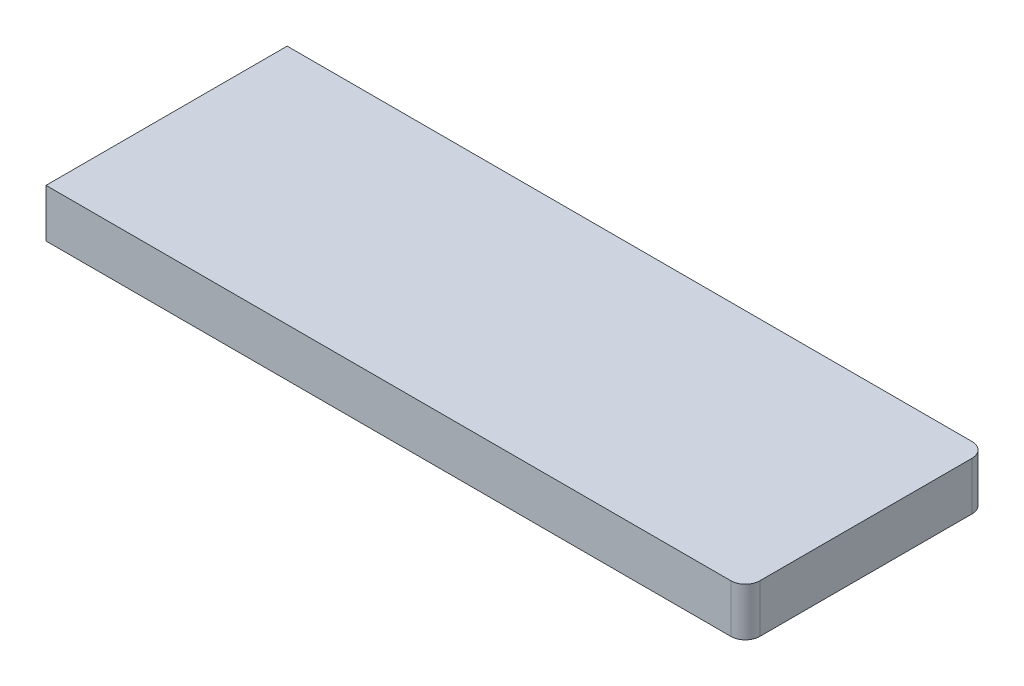
SolidWorks part; units mm, degrees
ref_plane "Front Plane" through (0, 0, 0) normal (0, 0, 1) x (1, 0, 0)
ref_plane "Top Plane" through (0, 0, 0) normal (0, 1, 0) x (1, 0, 0)
ref_plane "Right Plane" through (0, 0, 0) normal (1, 0, 0) x (0, 0, -1)
sketch "Sketch1" plane through (0, 0, 0) normal (0, 1, 0) x (1, 0, 0)
  line L1 (-72.5, 25) -> (72.5, 25)
  line L2 (-72.5, 25) -> (-72.5, -25)
  line L3 (-72.5, -25) -> (72.5, -25)
  line L4 (72.5, 25) -> (72.5, -25)
  line L5 (-72.5, 25) -> (72.5, -25) construction
  line L6 (-72.5, -25) -> (72.5, 25) construction
  point P0 (0, 0)
  dimension "D1" = 145
  dimension "D2" = 50
extrude "Boss-Extrude1" add sketch "Sketch1" along normal blind 10
fillet "Fillet1" radius 3 2 edges at (72.5, 5, -25) (72.5, 5, 25)
